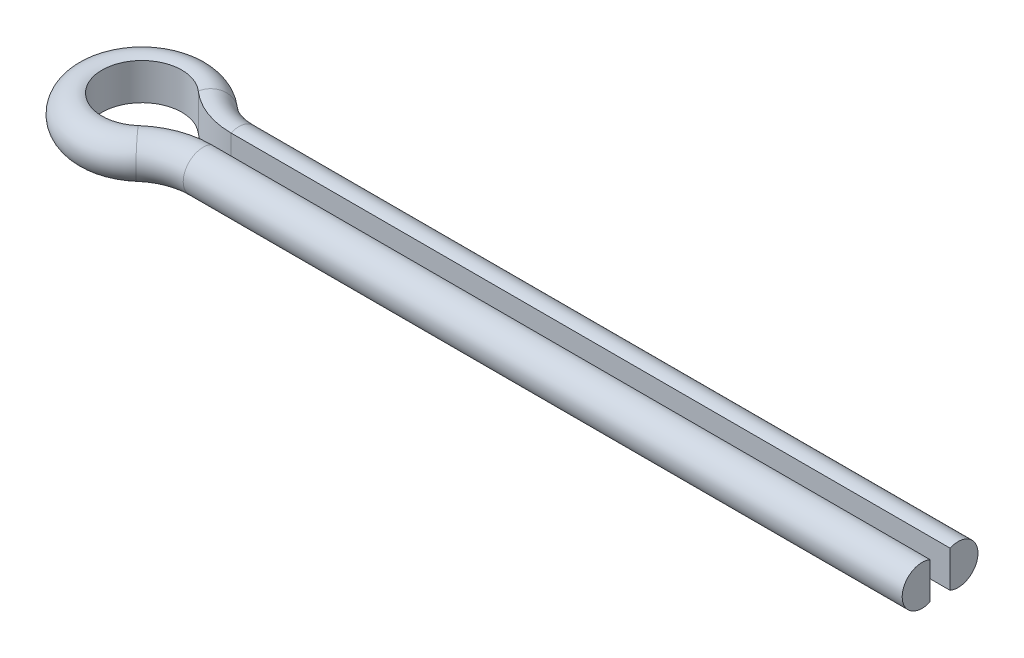
SolidWorks part; units mm, degrees
ref_plane "Front Plane" through (0, 0, 0) normal (0, 0, 1) x (1, 0, 0)
ref_plane "Top Plane" through (0, 0, 0) normal (0, 1, 0) x (1, 0, 0)
ref_plane "Right Plane" through (0, 0, 0) normal (1, 0, 0) x (0, 0, -1)
sketch "Sketch2" plane through (0, 0, 0) normal (0, 1, 0) x (1, 0, 0)
  line L0 (0, 0) -> (-90.0784, 0)
  line L1 (-90.0784, 2.5) -> (0, 2.5)
  arc A0 (-90.0784, 0) -> (-96.6928, -2.5) centre (-90.0784, -10) ccw
  arc A1 (-96.6928, -2.5) -> (-96.6928, 5) centre (-100, 1.25) cw
  arc A2 (-96.6928, 5) -> (-90.0784, 2.5) centre (-90.0784, 12.5) ccw
  point P9 (-105.1939, 17.9276)
  point P10 (-90.6844, 0)
  point P12 (-96.265, 0)
  dimension "D2" = 5
  dimension "D3" = 10
  dimension "D4" = 100
  dimension "D1" = 2.5
sketch "Sketch11" plane through (0, 0, 0) normal (1, 0, 0) x (0, 0, -1)
  line L0 (0, -2.2913) -> (0, 2.2913)
  arc A0 (0, -2.2913) -> (0, 2.2913) centre (-1, 0) cw
  point P3 (-3.5, 0)
  point P4 (0, 0)
  dimension "D2" = 2.5
  dimension "D1" = 3.5
sweep "Sweep2" add profiles "Sketch11" path "Sketch2"
